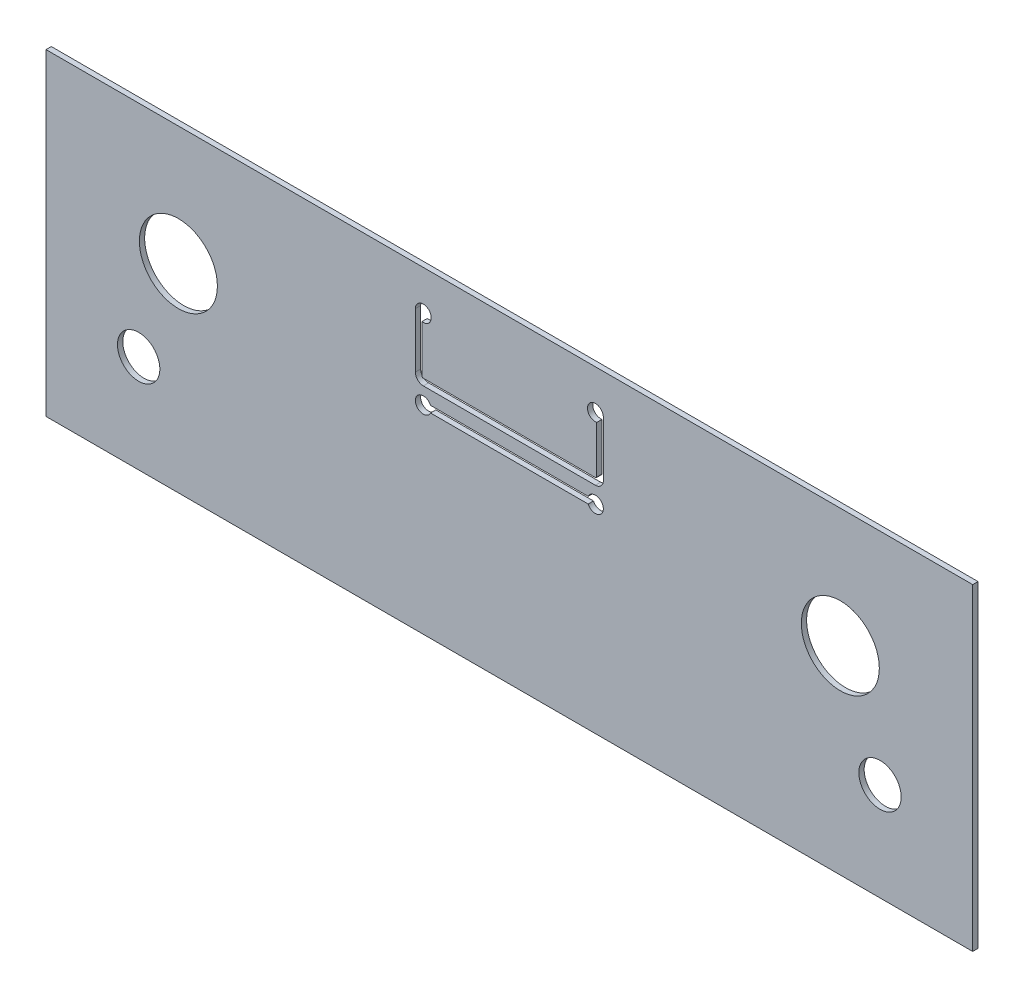
SolidWorks part; units mm, degrees
ref_plane "Front Plane" through (0, 0, 0) normal (0, 0, 1) x (1, 0, 0)
ref_plane "Top Plane" through (0, 0, 0) normal (0, 1, 0) x (1, 0, 0)
ref_plane "Right Plane" through (0, 0, 0) normal (1, 0, 0) x (0, 0, -1)
sketch "Sketch1" plane through (0, 0, 0) normal (0, 0, 1) x (1, 0, 0)
  line L0 (0, 0) -> (35, 0)
  line L1 (35, 0) -> (35, -12)
  line L2 (35, -12) -> (0, -12)
  line L3 (0, -12) -> (0, 0)
  line L5 (17.5, 4.0959) -> (17.5, -15.1104) construction
  line L6 (14.2, -1.7958) -> (14.2, -3.575)
  line L7 (14.25, -3.625) -> (20.75, -3.625)
  line L8 (20.8, -3.575) -> (20.8, -1.7958)
  line L9 (13.95, -1.5) -> (13.95, -3.575)
  line L10 (14.25, -3.875) -> (20.75, -3.875)
  line L11 (21.05, -3.575) -> (21.05, -1.5)
  line L12 (17.5, -3.625) -> (17.5, -3.875) construction
  line L13 (17.5, -3.625) -> (17.5, -3.875) construction
  line L14 (20.4773, -4.375) -> (14.5227, -4.375)
  line L15 (14.5227, -4.625) -> (20.4773, -4.625)
  circle A0 centre (3.5, -8.3) radius 0.8001
  circle A1 centre (5, -4.5) radius 1.4732
  arc A2 (14.2, -1.7958) -> (13.95, -1.5) centre (14.25, -1.5) ccw
  arc A3 (21.05, -1.5) -> (20.8, -1.7958) centre (20.75, -1.5) ccw
  arc A4 (20.4773, -4.625) -> (20.4773, -4.375) centre (20.75, -4.5) ccw
  arc A5 (14.5227, -4.375) -> (14.5227, -4.625) centre (14.25, -4.5) ccw
  circle A6 centre (30, -4.5) radius 1.4732
  circle A7 centre (31.5, -8.3) radius 0.8001
  arc A8 (14.2, -3.575) -> (14.25, -3.625) centre (14.25, -3.575) ccw
  arc A9 (20.75, -3.625) -> (20.8, -3.575) centre (20.75, -3.575) ccw
  arc A10 (13.95, -3.575) -> (14.25, -3.875) centre (14.25, -3.575) ccw
  arc A11 (20.75, -3.875) -> (21.05, -3.575) centre (20.75, -3.575) ccw
  point P14 (17.5, 0)
  point P47 (17.5, -3.75)
  dimension "D5" = 6.5
  dimension "D13" = 3
  dimension "D18" = 4.5
  dimension "D32" = 1.6002
  dimension "D34" = 2.9464
  dimension "D10" = 3.75
  dimension "D14" = 1.5
  dimension "D20" = 14.25
  dimension "D12" = 0.25
  dimension "D15" = 0.3
  dimension "D11" = 0.3
  dimension "D1" = 35
  dimension "D2" = 12
  dimension "D4" = 3.5
  dimension "D6" = 3.5
  dimension "D7" = 0.25
  dimension "D8" = 0.25
  dimension "D9" = 0.25
  dimension "D16" = 8.3
  dimension "D17" = 5
  dimension "D19" = 0.5
  dimension "D21" = 5
extrude "Boss-Extrude1" add sketch "Sketch1" along normal blind 0.2
